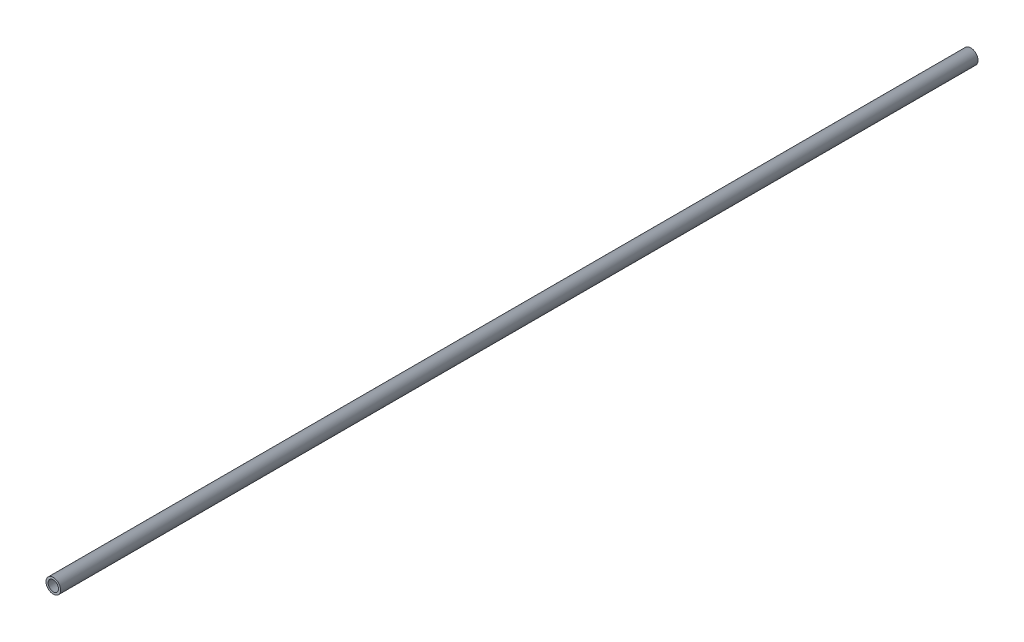
SolidWorks part; units mm, degrees
material "BLADE_CFRP_1550_PROVISIONAL"
ref_plane "Front Plane" through (0, 0, 0) normal (0, 0, 1) x (1, 0, 0)
ref_plane "Top Plane" through (0, 0, 0) normal (0, 1, 0) x (1, 0, 0)
ref_plane "Right Plane" through (0, 0, 0) normal (1, 0, 0) x (0, 0, -1)
sketch "Sketch1" plane through (0, 0, 0) normal (0, 0, 1) x (1, 0, 0)
  line L0 (11.2487, -0.0687) -> (11.2446, -0.1373)
  line L1 (11.2446, -0.1373) -> (11.2379, -0.2057)
  line L2 (11.2379, -0.2057) -> (11.2285, -0.2738)
  line L3 (11.2285, -0.2738) -> (11.2164, -0.3414)
  line L4 (11.2164, -0.3414) -> (11.2016, -0.4085)
  line L5 (11.2016, -0.4085) -> (11.1843, -0.475)
  line L6 (11.1843, -0.475) -> (11.1643, -0.5408)
  line L7 (11.1643, -0.5408) -> (11.1418, -0.6057)
  line L8 (11.1418, -0.6057) -> (11.1168, -0.6697)
  line L9 (11.1168, -0.6697) -> (11.0893, -0.7327)
  line L10 (11.0893, -0.7327) -> (11.0593, -0.7945)
  line L11 (11.0593, -0.7945) -> (11.0269, -0.8551)
  line L12 (11.0269, -0.8551) -> (10.9921, -0.9144)
  line L13 (10.9921, -0.9144) -> (10.9551, -0.9722)
  line L14 (10.9551, -0.9722) -> (10.9158, -1.0286)
  line L15 (10.9158, -1.0286) -> (10.8743, -1.0834)
  line L16 (10.8743, -1.0834) -> (10.8307, -1.1365)
  line L17 (10.8307, -1.1365) -> (10.7851, -1.1879)
  line L18 (10.7851, -1.1879) -> (10.7374, -1.2374)
  line L19 (10.7374, -1.2374) -> (10.6879, -1.2851)
  line L20 (10.6879, -1.2851) -> (10.6365, -1.3307)
  line L21 (10.6365, -1.3307) -> (10.5834, -1.3743)
  line L22 (10.5834, -1.3743) -> (10.5286, -1.4158)
  line L23 (10.5286, -1.4158) -> (10.4722, -1.4551)
  line L24 (10.4722, -1.4551) -> (10.4144, -1.4921)
  line L25 (10.4144, -1.4921) -> (10.3551, -1.5269)
  line L26 (10.3551, -1.5269) -> (10.2945, -1.5593)
  line L27 (10.2945, -1.5593) -> (10.2327, -1.5893)
  line L28 (10.2327, -1.5893) -> (10.1697, -1.6168)
  line L29 (10.1697, -1.6168) -> (10.1057, -1.6418)
  line L30 (10.1057, -1.6418) -> (10.0408, -1.6643)
  line L31 (10.0408, -1.6643) -> (9.975, -1.6843)
  line L32 (9.975, -1.6843) -> (9.9085, -1.7016)
  line L33 (9.9085, -1.7016) -> (9.8414, -1.7164)
  line L34 (9.8414, -1.7164) -> (9.7738, -1.7285)
  line L35 (9.7738, -1.7285) -> (9.7057, -1.7379)
  line L36 (9.7057, -1.7379) -> (9.6373, -1.7446)
  line L37 (9.6373, -1.7446) -> (9.5687, -1.7487)
  line L38 (9.5687, -1.7487) -> (9.5, -1.75)
  line L39 (9.5, -1.75) -> (9.4313, -1.7487)
  line L40 (9.4313, -1.7487) -> (9.3627, -1.7446)
  line L41 (9.3627, -1.7446) -> (9.2943, -1.7379)
  line L42 (9.2943, -1.7379) -> (9.2262, -1.7285)
  line L43 (9.2262, -1.7285) -> (9.1586, -1.7164)
  line L44 (9.1586, -1.7164) -> (9.0915, -1.7016)
  line L45 (9.0915, -1.7016) -> (9.025, -1.6843)
  line L46 (9.025, -1.6843) -> (8.9592, -1.6643)
  line L47 (8.9592, -1.6643) -> (8.8943, -1.6418)
  line L48 (8.8943, -1.6418) -> (8.8303, -1.6168)
  line L49 (8.8303, -1.6168) -> (8.7673, -1.5893)
  line L50 (8.7673, -1.5893) -> (8.7055, -1.5593)
  line L51 (8.7055, -1.5593) -> (8.6449, -1.5269)
  line L52 (8.6449, -1.5269) -> (8.5856, -1.4921)
  line L53 (8.5856, -1.4921) -> (8.5278, -1.4551)
  line L54 (8.5278, -1.4551) -> (8.4714, -1.4158)
  line L55 (8.4714, -1.4158) -> (8.4166, -1.3743)
  line L56 (8.4166, -1.3743) -> (8.3635, -1.3307)
  line L57 (8.3635, -1.3307) -> (8.3121, -1.2851)
  line L58 (8.3121, -1.2851) -> (8.2626, -1.2374)
  line L59 (8.2626, -1.2374) -> (8.2149, -1.1879)
  line L60 (8.2149, -1.1879) -> (8.1693, -1.1365)
  line L61 (8.1693, -1.1365) -> (8.1257, -1.0834)
  line L62 (8.1257, -1.0834) -> (8.0842, -1.0286)
  line L63 (8.0842, -1.0286) -> (8.0449, -0.9722)
  line L64 (8.0449, -0.9722) -> (8.0079, -0.9144)
  line L65 (8.0079, -0.9144) -> (7.9731, -0.8551)
  line L66 (7.9731, -0.8551) -> (7.9407, -0.7945)
  line L67 (7.9407, -0.7945) -> (7.9107, -0.7327)
  line L68 (7.9107, -0.7327) -> (7.8832, -0.6697)
  line L69 (7.8832, -0.6697) -> (7.8582, -0.6057)
  line L70 (7.8582, -0.6057) -> (7.8357, -0.5408)
  line L71 (7.8357, -0.5408) -> (7.8157, -0.475)
  line L72 (7.8157, -0.475) -> (7.7984, -0.4085)
  line L73 (7.7984, -0.4085) -> (7.7836, -0.3414)
  line L74 (7.7836, -0.3414) -> (7.7715, -0.2738)
  line L75 (7.7715, -0.2738) -> (7.7621, -0.2057)
  line L76 (7.7621, -0.2057) -> (7.7554, -0.1373)
  line L77 (7.7554, -0.1373) -> (7.7513, -0.0687)
  line L78 (7.7513, -0.0687) -> (7.75, 0)
  line L79 (7.75, 0) -> (7.7513, 0.0687)
  line L80 (7.7513, 0.0687) -> (7.7554, 0.1373)
  line L81 (7.7554, 0.1373) -> (7.7621, 0.2057)
  line L82 (7.7621, 0.2057) -> (7.7715, 0.2738)
  line L83 (7.7715, 0.2738) -> (7.7836, 0.3414)
  line L84 (7.7836, 0.3414) -> (7.7984, 0.4085)
  line L85 (7.7984, 0.4085) -> (7.8157, 0.475)
  line L86 (7.8157, 0.475) -> (7.8357, 0.5408)
  line L87 (7.8357, 0.5408) -> (7.8582, 0.6057)
  line L88 (7.8582, 0.6057) -> (7.8832, 0.6697)
  line L89 (7.8832, 0.6697) -> (7.9107, 0.7327)
  line L90 (7.9107, 0.7327) -> (7.9407, 0.7945)
  line L91 (7.9407, 0.7945) -> (7.9731, 0.8551)
  line L92 (7.9731, 0.8551) -> (8.0079, 0.9144)
  line L93 (8.0079, 0.9144) -> (8.0449, 0.9722)
  line L94 (8.0449, 0.9722) -> (8.0842, 1.0286)
  line L95 (8.0842, 1.0286) -> (8.1257, 1.0834)
  line L96 (8.1257, 1.0834) -> (8.1693, 1.1365)
  line L97 (8.1693, 1.1365) -> (8.2149, 1.1879)
  line L98 (8.2149, 1.1879) -> (8.2626, 1.2374)
  line L99 (8.2626, 1.2374) -> (8.3121, 1.2851)
  line L100 (8.3121, 1.2851) -> (8.3635, 1.3307)
  line L101 (8.3635, 1.3307) -> (8.4166, 1.3743)
  line L102 (8.4166, 1.3743) -> (8.4714, 1.4158)
  line L103 (8.4714, 1.4158) -> (8.5278, 1.4551)
  line L104 (8.5278, 1.4551) -> (8.5856, 1.4921)
  line L105 (8.5856, 1.4921) -> (8.6449, 1.5269)
  line L106 (8.6449, 1.5269) -> (8.7055, 1.5593)
  line L107 (8.7055, 1.5593) -> (8.7673, 1.5893)
  line L108 (8.7673, 1.5893) -> (8.8303, 1.6168)
  line L109 (8.8303, 1.6168) -> (8.8943, 1.6418)
  line L110 (8.8943, 1.6418) -> (8.9592, 1.6643)
  line L111 (8.9592, 1.6643) -> (9.025, 1.6843)
  line L112 (9.025, 1.6843) -> (9.0915, 1.7016)
  line L113 (9.0915, 1.7016) -> (9.1586, 1.7164)
  line L114 (9.1586, 1.7164) -> (9.2262, 1.7285)
  line L115 (9.2262, 1.7285) -> (9.2943, 1.7379)
  line L116 (9.2943, 1.7379) -> (9.3627, 1.7446)
  line L117 (9.3627, 1.7446) -> (9.4313, 1.7487)
  line L118 (9.4313, 1.7487) -> (9.5, 1.75)
  line L119 (9.5, 1.75) -> (9.5687, 1.7487)
  line L120 (9.5687, 1.7487) -> (9.6373, 1.7446)
  line L121 (9.6373, 1.7446) -> (9.7057, 1.7379)
  line L122 (9.7057, 1.7379) -> (9.7738, 1.7285)
  line L123 (9.7738, 1.7285) -> (9.8414, 1.7164)
  line L124 (9.8414, 1.7164) -> (9.9085, 1.7016)
  line L125 (9.9085, 1.7016) -> (9.975, 1.6843)
  line L126 (9.975, 1.6843) -> (10.0408, 1.6643)
  line L127 (10.0408, 1.6643) -> (10.1057, 1.6418)
  line L128 (10.1057, 1.6418) -> (10.1697, 1.6168)
  line L129 (10.1697, 1.6168) -> (10.2327, 1.5893)
  line L130 (10.2327, 1.5893) -> (10.2945, 1.5593)
  line L131 (10.2945, 1.5593) -> (10.3551, 1.5269)
  line L132 (10.3551, 1.5269) -> (10.4144, 1.4921)
  line L133 (10.4144, 1.4921) -> (10.4722, 1.4551)
  line L134 (10.4722, 1.4551) -> (10.5286, 1.4158)
  line L135 (10.5286, 1.4158) -> (10.5834, 1.3743)
  line L136 (10.5834, 1.3743) -> (10.6365, 1.3307)
  line L137 (10.6365, 1.3307) -> (10.6879, 1.2851)
  line L138 (10.6879, 1.2851) -> (10.7374, 1.2374)
  line L139 (10.7374, 1.2374) -> (10.7851, 1.1879)
  line L140 (10.7851, 1.1879) -> (10.8307, 1.1365)
  line L141 (10.8307, 1.1365) -> (10.8743, 1.0834)
  line L142 (10.8743, 1.0834) -> (10.9158, 1.0286)
  line L143 (10.9158, 1.0286) -> (10.9551, 0.9722)
  line L144 (10.9551, 0.9722) -> (10.9921, 0.9144)
  line L145 (10.9921, 0.9144) -> (11.0269, 0.8551)
  line L146 (11.0269, 0.8551) -> (11.0593, 0.7945)
  line L147 (11.0593, 0.7945) -> (11.0893, 0.7327)
  line L148 (11.0893, 0.7327) -> (11.1168, 0.6697)
  line L149 (11.1168, 0.6697) -> (11.1418, 0.6057)
  line L150 (11.1418, 0.6057) -> (11.1643, 0.5408)
  line L151 (11.1643, 0.5408) -> (11.1843, 0.475)
  line L152 (11.1843, 0.475) -> (11.2016, 0.4085)
  line L153 (11.2016, 0.4085) -> (11.2164, 0.3414)
  line L154 (11.2164, 0.3414) -> (11.2285, 0.2738)
  line L155 (11.2285, 0.2738) -> (11.2379, 0.2057)
  line L156 (11.2379, 0.2057) -> (11.2446, 0.1373)
  line L157 (11.2446, 0.1373) -> (11.2487, 0.0687)
  line L158 (11.2487, 0.0687) -> (11.25, 0)
  line L159 (11.25, 0) -> (11.2487, -0.0687)
  line L160 (10.749, 0.0491) -> (10.7461, 0.0981)
  line L161 (10.7461, 0.0981) -> (10.7413, 0.1469)
  line L162 (10.7413, 0.1469) -> (10.7346, 0.1955)
  line L163 (10.7346, 0.1955) -> (10.726, 0.2439)
  line L164 (10.726, 0.2439) -> (10.7155, 0.2918)
  line L165 (10.7155, 0.2918) -> (10.7031, 0.3393)
  line L166 (10.7031, 0.3393) -> (10.6888, 0.3863)
  line L167 (10.6888, 0.3863) -> (10.6727, 0.4326)
  line L168 (10.6727, 0.4326) -> (10.6548, 0.4784)
  line L169 (10.6548, 0.4784) -> (10.6352, 0.5233)
  line L170 (10.6352, 0.5233) -> (10.6138, 0.5675)
  line L171 (10.6138, 0.5675) -> (10.5906, 0.6108)
  line L172 (10.5906, 0.6108) -> (10.5658, 0.6531)
  line L173 (10.5658, 0.6531) -> (10.5393, 0.6945)
  line L174 (10.5393, 0.6945) -> (10.5113, 0.7347)
  line L175 (10.5113, 0.7347) -> (10.4816, 0.7739)
  line L176 (10.4816, 0.7739) -> (10.4505, 0.8118)
  line L177 (10.4505, 0.8118) -> (10.4179, 0.8485)
  line L178 (10.4179, 0.8485) -> (10.3839, 0.8839)
  line L179 (10.3839, 0.8839) -> (10.3485, 0.9179)
  line L180 (10.3485, 0.9179) -> (10.3118, 0.9505)
  line L181 (10.3118, 0.9505) -> (10.2739, 0.9816)
  line L182 (10.2739, 0.9816) -> (10.2347, 1.0113)
  line L183 (10.2347, 1.0113) -> (10.1945, 1.0393)
  line L184 (10.1945, 1.0393) -> (10.1531, 1.0658)
  line L185 (10.1531, 1.0658) -> (10.1108, 1.0906)
  line L186 (10.1108, 1.0906) -> (10.0675, 1.1138)
  line L187 (10.0675, 1.1138) -> (10.0233, 1.1352)
  line L188 (10.0233, 1.1352) -> (9.9784, 1.1548)
  line L189 (9.9784, 1.1548) -> (9.9326, 1.1727)
  line L190 (9.9326, 1.1727) -> (9.8863, 1.1888)
  line L191 (9.8863, 1.1888) -> (9.8393, 1.2031)
  line L192 (9.8393, 1.2031) -> (9.7918, 1.2155)
  line L193 (9.7918, 1.2155) -> (9.7439, 1.226)
  line L194 (9.7439, 1.226) -> (9.6955, 1.2346)
  line L195 (9.6955, 1.2346) -> (9.6469, 1.2413)
  line L196 (9.6469, 1.2413) -> (9.5981, 1.2461)
  line L197 (9.5981, 1.2461) -> (9.5491, 1.249)
  line L198 (9.5491, 1.249) -> (9.5, 1.25)
  line L199 (9.5, 1.25) -> (9.4509, 1.249)
  line L200 (9.4509, 1.249) -> (9.4019, 1.2461)
  line L201 (9.4019, 1.2461) -> (9.3531, 1.2413)
  line L202 (9.3531, 1.2413) -> (9.3045, 1.2346)
  line L203 (9.3045, 1.2346) -> (9.2561, 1.226)
  line L204 (9.2561, 1.226) -> (9.2082, 1.2155)
  line L205 (9.2082, 1.2155) -> (9.1607, 1.2031)
  line L206 (9.1607, 1.2031) -> (9.1137, 1.1888)
  line L207 (9.1137, 1.1888) -> (9.0674, 1.1727)
  line L208 (9.0674, 1.1727) -> (9.0216, 1.1548)
  line L209 (9.0216, 1.1548) -> (8.9767, 1.1352)
  line L210 (8.9767, 1.1352) -> (8.9325, 1.1138)
  line L211 (8.9325, 1.1138) -> (8.8892, 1.0906)
  line L212 (8.8892, 1.0906) -> (8.8469, 1.0658)
  line L213 (8.8469, 1.0658) -> (8.8055, 1.0393)
  line L214 (8.8055, 1.0393) -> (8.7653, 1.0113)
  line L215 (8.7653, 1.0113) -> (8.7261, 0.9816)
  line L216 (8.7261, 0.9816) -> (8.6882, 0.9505)
  line L217 (8.6882, 0.9505) -> (8.6515, 0.9179)
  line L218 (8.6515, 0.9179) -> (8.6161, 0.8839)
  line L219 (8.6161, 0.8839) -> (8.5821, 0.8485)
  line L220 (8.5821, 0.8485) -> (8.5495, 0.8118)
  line L221 (8.5495, 0.8118) -> (8.5184, 0.7739)
  line L222 (8.5184, 0.7739) -> (8.4887, 0.7347)
  line L223 (8.4887, 0.7347) -> (8.4607, 0.6945)
  line L224 (8.4607, 0.6945) -> (8.4342, 0.6531)
  line L225 (8.4342, 0.6531) -> (8.4094, 0.6108)
  line L226 (8.4094, 0.6108) -> (8.3862, 0.5675)
  line L227 (8.3862, 0.5675) -> (8.3648, 0.5233)
  line L228 (8.3648, 0.5233) -> (8.3452, 0.4784)
  line L229 (8.3452, 0.4784) -> (8.3273, 0.4326)
  line L230 (8.3273, 0.4326) -> (8.3112, 0.3863)
  line L231 (8.3112, 0.3863) -> (8.2969, 0.3393)
  line L232 (8.2969, 0.3393) -> (8.2845, 0.2918)
  line L233 (8.2845, 0.2918) -> (8.274, 0.2439)
  line L234 (8.274, 0.2439) -> (8.2654, 0.1955)
  line L235 (8.2654, 0.1955) -> (8.2587, 0.1469)
  line L236 (8.2587, 0.1469) -> (8.2539, 0.0981)
  line L237 (8.2539, 0.0981) -> (8.251, 0.0491)
  line L238 (8.251, 0.0491) -> (8.25, 0)
  line L239 (8.25, 0) -> (8.251, -0.0491)
  line L240 (8.251, -0.0491) -> (8.2539, -0.0981)
  line L241 (8.2539, -0.0981) -> (8.2587, -0.1469)
  line L242 (8.2587, -0.1469) -> (8.2654, -0.1955)
  line L243 (8.2654, -0.1955) -> (8.274, -0.2439)
  line L244 (8.274, -0.2439) -> (8.2845, -0.2918)
  line L245 (8.2845, -0.2918) -> (8.2969, -0.3393)
  line L246 (8.2969, -0.3393) -> (8.3112, -0.3863)
  line L247 (8.3112, -0.3863) -> (8.3273, -0.4326)
  line L248 (8.3273, -0.4326) -> (8.3452, -0.4784)
  line L249 (8.3452, -0.4784) -> (8.3648, -0.5233)
  line L250 (8.3648, -0.5233) -> (8.3862, -0.5675)
  line L251 (8.3862, -0.5675) -> (8.4094, -0.6108)
  line L252 (8.4094, -0.6108) -> (8.4342, -0.6531)
  line L253 (8.4342, -0.6531) -> (8.4607, -0.6945)
  line L254 (8.4607, -0.6945) -> (8.4887, -0.7347)
  line L255 (8.4887, -0.7347) -> (8.5184, -0.7739)
  line L256 (8.5184, -0.7739) -> (8.5495, -0.8118)
  line L257 (8.5495, -0.8118) -> (8.5821, -0.8485)
  line L258 (8.5821, -0.8485) -> (8.6161, -0.8839)
  line L259 (8.6161, -0.8839) -> (8.6515, -0.9179)
  line L260 (8.6515, -0.9179) -> (8.6882, -0.9505)
  line L261 (8.6882, -0.9505) -> (8.7261, -0.9816)
  line L262 (8.7261, -0.9816) -> (8.7653, -1.0113)
  line L263 (8.7653, -1.0113) -> (8.8055, -1.0393)
  line L264 (8.8055, -1.0393) -> (8.8469, -1.0658)
  line L265 (8.8469, -1.0658) -> (8.8892, -1.0906)
  line L266 (8.8892, -1.0906) -> (8.9325, -1.1138)
  line L267 (8.9325, -1.1138) -> (8.9767, -1.1352)
  line L268 (8.9767, -1.1352) -> (9.0216, -1.1548)
  line L269 (9.0216, -1.1548) -> (9.0674, -1.1727)
  line L270 (9.0674, -1.1727) -> (9.1137, -1.1888)
  line L271 (9.1137, -1.1888) -> (9.1607, -1.2031)
  line L272 (9.1607, -1.2031) -> (9.2082, -1.2155)
  line L273 (9.2082, -1.2155) -> (9.2561, -1.226)
  line L274 (9.2561, -1.226) -> (9.3045, -1.2346)
  line L275 (9.3045, -1.2346) -> (9.3531, -1.2413)
  line L276 (9.3531, -1.2413) -> (9.4019, -1.2461)
  line L277 (9.4019, -1.2461) -> (9.4509, -1.249)
  line L278 (9.4509, -1.249) -> (9.5, -1.25)
  line L279 (9.5, -1.25) -> (9.5491, -1.249)
  line L280 (9.5491, -1.249) -> (9.5981, -1.2461)
  line L281 (9.5981, -1.2461) -> (9.6469, -1.2413)
  line L282 (9.6469, -1.2413) -> (9.6955, -1.2346)
  line L283 (9.6955, -1.2346) -> (9.7439, -1.226)
  line L284 (9.7439, -1.226) -> (9.7918, -1.2155)
  line L285 (9.7918, -1.2155) -> (9.8393, -1.2031)
  line L286 (9.8393, -1.2031) -> (9.8863, -1.1888)
  line L287 (9.8863, -1.1888) -> (9.9326, -1.1727)
  line L288 (9.9326, -1.1727) -> (9.9784, -1.1548)
  line L289 (9.9784, -1.1548) -> (10.0233, -1.1352)
  line L290 (10.0233, -1.1352) -> (10.0675, -1.1138)
  line L291 (10.0675, -1.1138) -> (10.1108, -1.0906)
  line L292 (10.1108, -1.0906) -> (10.1531, -1.0658)
  line L293 (10.1531, -1.0658) -> (10.1945, -1.0393)
  line L294 (10.1945, -1.0393) -> (10.2347, -1.0113)
  line L295 (10.2347, -1.0113) -> (10.2739, -0.9816)
  line L296 (10.2739, -0.9816) -> (10.3118, -0.9505)
  line L297 (10.3118, -0.9505) -> (10.3485, -0.9179)
  line L298 (10.3485, -0.9179) -> (10.3839, -0.8839)
  line L299 (10.3839, -0.8839) -> (10.4179, -0.8485)
  line L300 (10.4179, -0.8485) -> (10.4505, -0.8118)
  line L301 (10.4505, -0.8118) -> (10.4816, -0.7739)
  line L302 (10.4816, -0.7739) -> (10.5113, -0.7347)
  line L303 (10.5113, -0.7347) -> (10.5393, -0.6945)
  line L304 (10.5393, -0.6945) -> (10.5658, -0.6531)
  line L305 (10.5658, -0.6531) -> (10.5906, -0.6108)
  line L306 (10.5906, -0.6108) -> (10.6138, -0.5675)
  line L307 (10.6138, -0.5675) -> (10.6352, -0.5233)
  line L308 (10.6352, -0.5233) -> (10.6548, -0.4784)
  line L309 (10.6548, -0.4784) -> (10.6727, -0.4326)
  line L310 (10.6727, -0.4326) -> (10.6888, -0.3863)
  line L311 (10.6888, -0.3863) -> (10.7031, -0.3393)
  line L312 (10.7031, -0.3393) -> (10.7155, -0.2918)
  line L313 (10.7155, -0.2918) -> (10.726, -0.2439)
  line L314 (10.726, -0.2439) -> (10.7346, -0.1955)
  line L315 (10.7346, -0.1955) -> (10.7413, -0.1469)
  line L316 (10.7413, -0.1469) -> (10.7461, -0.0981)
  line L317 (10.7461, -0.0981) -> (10.749, -0.0491)
  line L318 (10.749, -0.0491) -> (10.75, 0)
  line L319 (10.75, 0) -> (10.749, 0.0491)
extrude "Defined_Material_Section_L220" add sketch "Sketch1" along normal blind 220
